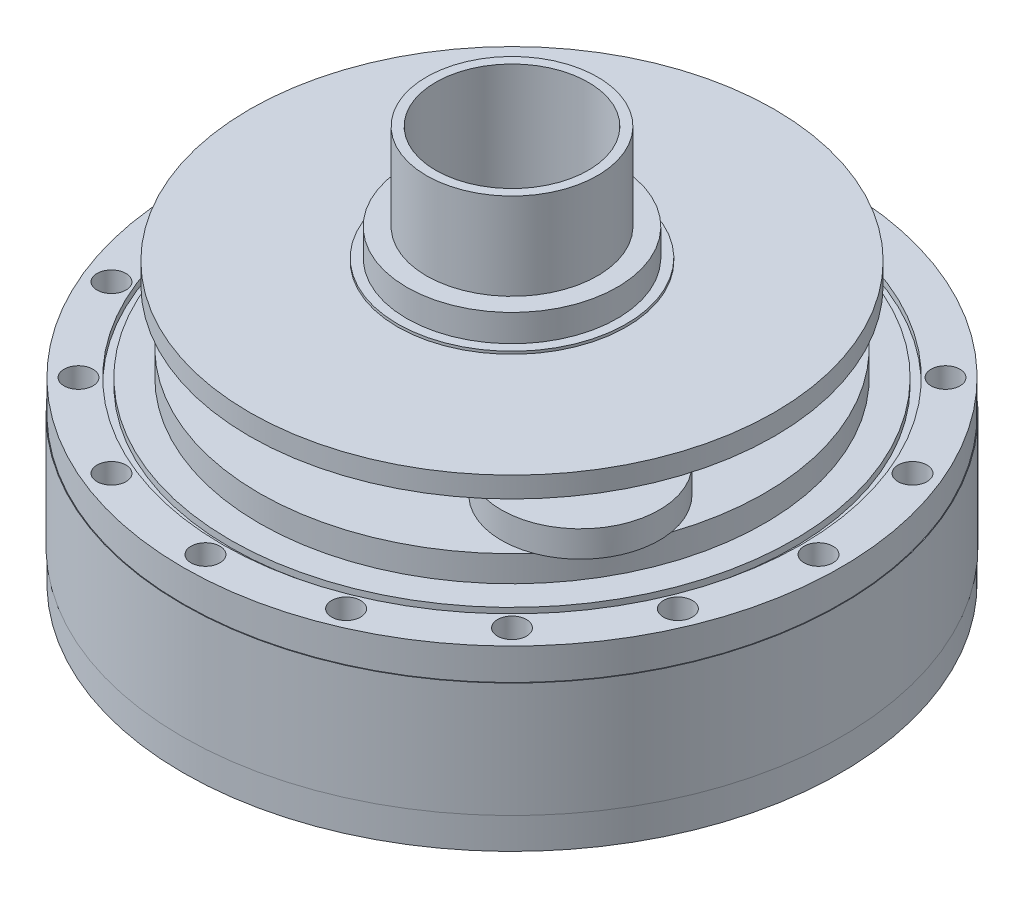
SolidWorks part; units mm, degrees
ref_plane "Front Plane" through (0, 0, 0) normal (0, 0, 1) x (1, 0, 0)
ref_plane "Top Plane" through (0, 0, 0) normal (0, 1, 0) x (1, 0, 0)
ref_plane "Right Plane" through (0, 0, 0) normal (1, 0, 0) x (0, 0, -1)
sketch "Sketch1" plane through (0, 0, 0) normal (1, 0, 0) x (0, 0, -1)
  line L0 (-29, 0) -> (-99.5, 0)
  line L1 (-99.5, 0) -> (-99.5, 5)
  line L2 (-99.5, 5) -> (-125, 5)
  line L3 (-125, 5) -> (-125, 17)
  line L4 (-125, 17) -> (-125.25, 17)
  line L5 (-125.25, 17) -> (-125.25, 60.6)
  line L7 (-125, 60.6) -> (-125, 72.6)
  line L8 (-125, 72.6) -> (-110, 72.6)
  line L9 (-96, 72.6) -> (-96, 82.5)
  line L10 (-96, 82.5) -> (-40, 82.5)
  line L13 (-40, 82.5) -> (-40, 103.15)
  line L14 (-40, 103.15) -> (-99.75, 103.15)
  line L15 (-99.75, 103.15) -> (-99.75, 111)
  line L16 (-99.75, 111) -> (-43.5, 111)
  line L17 (-40, 112) -> (-40, 122.3)
  line L18 (-40, 122.3) -> (-32.5, 122.3)
  line L20 (-43.5, 111) -> (-43.5, 112)
  line L21 (0, 155.3) -> (0, 0) construction
  line L22 (-125, 60.6) -> (-125.25, 60.6)
  line L23 (-110, 72.6) -> (-110, 70.1)
  line L24 (-110, 70.1) -> (-107, 70.1)
  line L25 (-107, 70.1) -> (-107, 72.6)
  line L26 (-107, 72.6) -> (-96, 72.6)
  line L27 (-32.5, 122.3) -> (-32.5, 155.3)
  line L28 (-32.5, 155.3) -> (-29, 155.3)
  line L29 (-29, 155.3) -> (-29, 0)
  line L30 (-43.5, 112) -> (-40, 112)
  dimension "D1" = 199
  dimension "D2" = 250
  dimension "D3" = 250.5
  dimension "D4" = 250
  dimension "D5" = 80
  dimension "D6" = 199.5
  dimension "D7" = 58
  dimension "D8" = 65
  dimension "D9" = 5
  dimension "D10" = 12
  dimension "D11" = 12
  dimension "D12" = 67.6
  dimension "D13" = 82.5
  dimension "D14" = 38.4
  dimension "D15" = 7.85
  dimension "D16" = 214
  dimension "D17" = 220
  dimension "D18" = 2.5
  dimension "D19" = 192
  dimension "D20" = 1
  dimension "D21" = 11.3
  dimension "D22" = 33
  dimension "D23" = 87
revolve "Revolve1" add sketch "Sketch1" angle 360 about L21
sketch "Sketch2" plane through (0, 0, 0) normal (0, -1, 0) x (1, 0, 0)
  circle A0 centre (0, 0) radius 53
  dimension "D1" = 106
extrude "Cut-Extrude1" cut sketch "Sketch2" against normal blind 13
sketch "Sketch3" plane through (0, 5, 0) normal (0, -1, 0) x (1, 0, 0)
  line L0 (0, 0) -> (-173.047, 0) construction
  line L1 (0, 0) -> (-116.5, 0) construction
  line L2 (0, 0) -> (-107.632, 44.5826) construction
  circle A0 centre (0, 0) radius 116.5 construction
  circle A1 centre (-116.5, 0) radius 5.5
  circle A2 centre (-107.632, 44.5826) radius 5.5
  circle A3 centre (-82.3779, 82.3779) radius 5.5
  circle A4 centre (-44.5826, 107.632) radius 5.5
  circle A5 centre (0, 116.5) radius 5.5
  circle A6 centre (44.5826, 107.632) radius 5.5
  circle A7 centre (82.3779, 82.3779) radius 5.5
  circle A8 centre (107.632, 44.5826) radius 5.5
  circle A9 centre (116.5, 0) radius 5.5
  circle A10 centre (107.632, -44.5826) radius 5.5
  circle A11 centre (82.3779, -82.3779) radius 5.5
  circle A13 centre (0, -116.5) radius 5.5
  circle A14 centre (-44.5826, -107.632) radius 5.5
  circle A15 centre (-82.3779, -82.3779) radius 5.5
  circle A16 centre (44.5826, -107.632) radius 5.5 [skipped]
  dimension "D1" = 11
  dimension "D2" = 233
  dimension "D4" = 22.5
  dimension "D3" = 15
extrude "Cut-Extrude2" cut sketch "Sketch3" against normal through all
sketch "Sketch4" plane through (0, 0, 0) normal (0, -1, 0) x (-1, 0, 0)
  line L0 (0, 0) -> (180.6416, 0) construction
  line L1 (0, 0) -> (80, 0) construction
  line L2 (0, 0) -> (69.282, -40) construction
  circle A0 centre (0, 0) radius 80 construction
  circle A1 centre (80, 0) radius 6
  circle A2 centre (69.282, -40) radius 6
  circle A4 centre (0, -80) radius 6
  circle A5 centre (-40, -69.282) radius 6
  circle A6 centre (-69.282, -40) radius 6
  circle A8 centre (-69.282, 40) radius 6
  circle A9 centre (-40, 69.282) radius 6
  circle A10 centre (0, 80) radius 6
  circle A12 centre (69.282, 40) radius 6
  circle A13 centre (40, -69.282) radius 6 [skipped]
  circle A14 centre (-80, 0) radius 6 [skipped]
  circle A15 centre (40, 69.282) radius 6 [skipped]
  point P6 (0, -66.1259)
  point P7 (0, 1.9937)
  dimension "D1" = 160
  dimension "D2" = 12
  dimension "D4" = 30
  dimension "D3" = 12
extrude "Cut-Extrude3" cut sketch "Sketch4" against normal blind 20 contours A2
sketch "Sketch5" plane through (0, 82.5, 0) normal (0, 1, 0) x (1, 0, 0)
  line L0 (0, 71) -> (0, 0) construction
  circle A0 centre (0, 0) radius 101 construction
  circle A1 centre (0, 71) radius 30
  circle A2 centre (61.4878, -35.5) radius 30
  circle A3 centre (-61.4878, -35.5) radius 30
  point P12 (0, 0)
  dimension "D1" = 202
  dimension "D2" = 60
  dimension "D3" = 3
extrude "Boss-Extrude1" add sketch "Sketch5" along normal blind 10
